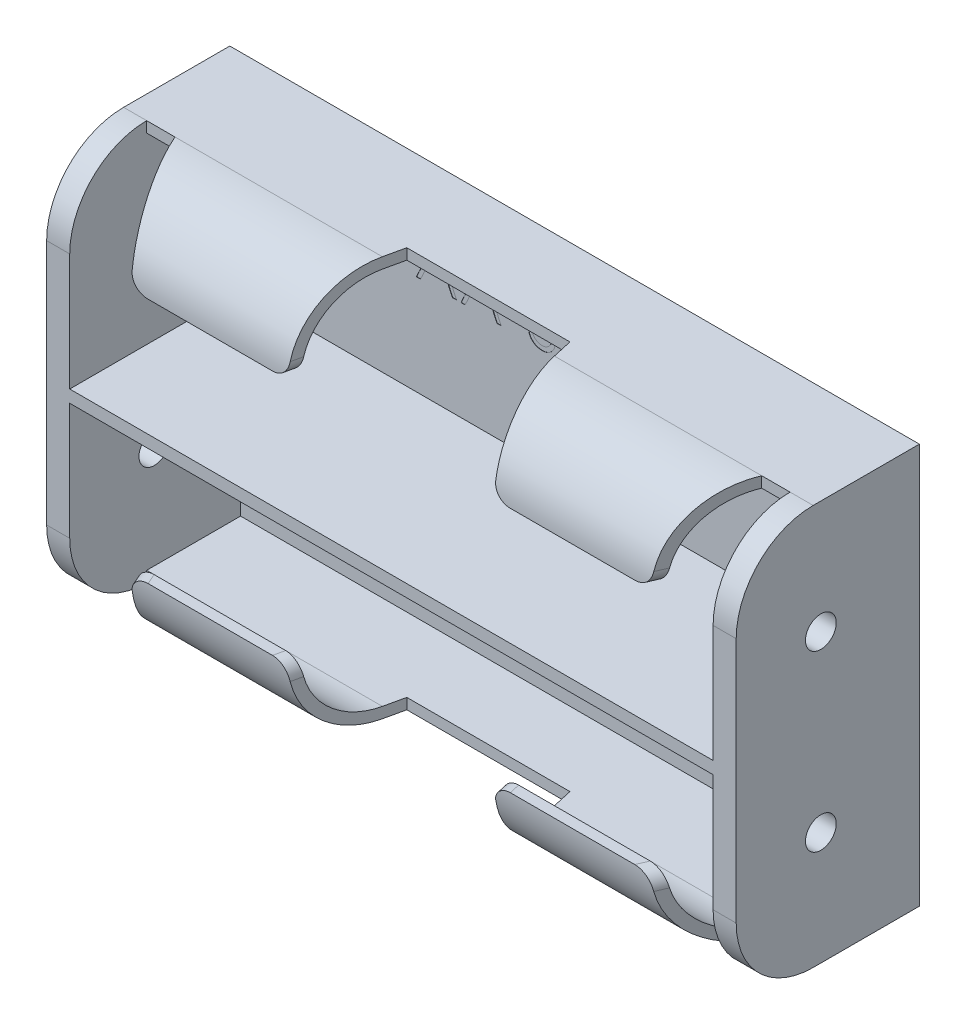
SolidWorks part; units mm, degrees
material "PTFE (general)"
ref_plane "Plane1" through (0, 0, 0) normal (0, 0, 1) x (1, 0, 0)
ref_plane "Plane2" through (0, 0, 0) normal (0, 1, 0) x (1, 0, 0)
ref_plane "Plane3" through (0, 0, 0) normal (1, 0, 0) x (0, 0, -1)
sketch "Sketch1" plane through (0, 0, 0) normal (0, 0, 1) x (1, 0, 0)
  line L0 (-28.448, -16.51) -> (28.448, 16.51) construction
  line L1 (-28.448, 16.51) -> (28.448, 16.51)
  line L2 (-28.448, 16.51) -> (-28.448, -16.51)
  line L3 (-28.448, -16.51) -> (28.448, -16.51)
  line L4 (28.448, 16.51) -> (28.448, -16.51)
  dimension "D1" = 56.896
  dimension "D2" = 33.02
extrude "Extrude1" add sketch "Sketch1" along normal blind 15.113
fillet "Fillet1" radius 6.35 2 edges at (0, 16.51, 15.113) (0, -16.51, 15.113)
sketch "Sketch2" plane through (0, 0, 0) normal (1, 0, 0) x (0, 0, -1)
  line L0 (-1.016, 15.621) -> (-1.016, 0.508)
  line L1 (-1.016, 0.508) -> (-15.113, 0.508)
  line L2 (-15.113, 0.508) -> (-15.113, 10.16)
  line L3 (-15.113, 10.16) -> (-14.224, 10.16)
  line L5 (-8.763, 15.621) -> (-1.016, 15.621)
  line L6 (0, -16.51) -> (0, 16.51) construction
  line L7 (-15.113, -10.16) -> (-15.113, 10.16) construction
  arc A2 (-8.763, 15.621) -> (-14.224, 10.16) centre (-8.763, 10.16) ccw
  arc A3 (-8.763, 15.621) -> (-14.224, 10.16) centre (-8.763, 10.16) ccw
  dimension "D2" = 0.508
  dimension "D3" = 1.016
  dimension "D1" = 0.889
extrude "Cut-Extrude1" cut sketch "Sketch2" against normal mid plane 53.086
sketch "Sketch3" plane through (0, 16.51, 0) normal (0, 1, 0) x (-1, 0, 0)
  line L0 (-8.509, 15.113) -> (8.509, 15.113)
  line L1 (8.509, 15.113) -> (6.731, 7.112)
  line L2 (6.731, 7.112) -> (-6.731, 7.112)
  line L3 (-6.731, 7.112) -> (-8.509, 15.113)
  line L4 (-28.448, 0) -> (28.448, 0) construction
  line L5 (0, 15.113) -> (0, 0) construction
  line L6 (0, 7.112) -> (0, 0) construction
  line L7 (26.543, 15.113) -> (-26.543, 15.113) construction
  line L8 (-26.543, 8.763) -> (-26.543, 14.224) construction
  line L9 (-26.543, 8.763) -> (-26.543, 15.113)
  line L10 (-26.543, 8.763) -> (-24.2062, 8.763)
  line L11 (28.448, 8.763) -> (-28.448, 8.763) construction
  line L12 (-24.2062, 8.763) -> (-21.463, 15.113)
  line L13 (-21.463, 15.113) -> (-26.543, 15.113)
  line L14 (26.543, 8.763) -> (24.2062, 8.763)
  line L15 (26.543, 8.763) -> (26.543, 15.113)
  line L16 (21.463, 15.113) -> (26.543, 15.113)
  line L17 (24.2062, 8.763) -> (21.463, 15.113)
  dimension "D1" = 7.112
  dimension "D2" = 17.018
  dimension "D3" = 13.462
  dimension "D4" = 2.3368
  dimension "D5" = 5.08
extrude "Cut-Extrude2" cut sketch "Sketch3" against normal blind 7.112
fillet "Fillet2" radius 1.27 4 edges at (-21.655, 10.16, 14.6685) (-8.4102, 10.16, 14.6685) (21.655, 10.16, 14.6685) (8.4102, 10.16, 14.6685)
sketch "Sketch4" plane through (0, 0, 0) normal (1, 0, 0) x (0, 0, -1)
  line L0 (0, -16.51) -> (0, 16.51) construction
  line L1 (-8.763, 16.51) -> (0, 16.51) construction
  circle A0 centre (-8.128, 7.1755) radius 1.27
  dimension "D1" = 8.128
  dimension "D2" = 9.3345
  dimension "D3" = 2.54
extrude "Cut-Extrude3" cut sketch "Sketch4" against normal mid plane 98.806
mirror "Mirror1" about plane through (0, 0, 0) normal (0, 1, 0) of "Cut-Extrude3", "Fillet2", "Cut-Extrude2", "Cut-Extrude1"
sketch "Sketch5" plane through (0, 0, 1.016) normal (0, 0, 1) x (1, 0, 0)
  text T0 "R6-AA-UM3-1.5V"
  text T1 "-"
  text T2 "+"
  text T3 "-"
  text T4 "+"
extrude "Cut-Extrude4" cut sketch "Sketch5" against normal blind 0.0254
ref_plane "Plane4" through (0, 2.032, 0) normal (0, 1, 0) x (-1, 0, 0)
sketch "Sketch6" plane through (-28.448, 0, 0) normal (-1, 0, 0) x (0, 0, 1)
  line L1 (8.3122, 2.032) -> (-8.3122, 2.032) construction
  circle A0 centre (0.8459, 2.032) radius 0.3535
sketch3d "3DSketch1"
  spline S0 degree 3 poles (-28.448, 2.032, 0.8459) (-33.5107, 2.6584, 0.4955) (-51.4952, 4.8836, -0.749) (-73.1551, -9.0891, 6.2524) (-85.8516, -4.3171, -1.7144) (-87.7639, -3.5983, -2.9143) knots 0 0 0 0 0.249691 0.88699 1 1 1 1
sketch "Sketch7" plane through (0, 0, 15.113) normal (0, 0, 1) x (1, 0, 0)
  line L0 (-26.543, 0.508) -> (-26.543, 15.621) construction
  line L1 (-26.543, 15.4305) -> (26.543, 15.4305)
  line L2 (-26.543, 15.4305) -> (-26.543, 14.4145)
  line L3 (-26.543, 14.4145) -> (26.543, 14.4145)
  line L4 (26.543, 15.4305) -> (26.543, 14.4145)
  line L5 (26.543, 10.16) -> (26.543, 0.508) construction
  line L6 (26.543, -0.508) -> (26.543, -15.621) construction
  line L7 (26.543, -14.4145) -> (-26.543, -14.4145)
  line L8 (26.543, -14.4145) -> (26.543, -15.4305)
  line L9 (26.543, -15.4305) -> (-26.543, -15.4305)
  line L10 (-26.543, -14.4145) -> (-26.543, -15.4305)
  line L11 (-26.543, -0.508) -> (-26.543, -15.621) construction
  line L12 (-26.543, 14.9225) -> (26.543, 14.9225) construction
  line L13 (-26.543, -14.9225) -> (26.543, -14.9225) construction
  line L14 (-28.448, 0) -> (28.448, 0) construction
  line L15 (-28.448, 10.16) -> (-28.448, -10.16) construction
  line L16 (28.448, -10.16) -> (28.448, 10.16) construction
  dimension "D2" = 14.9225
  dimension "D1" = 1.016
  dimension "D3" = 14.9225
